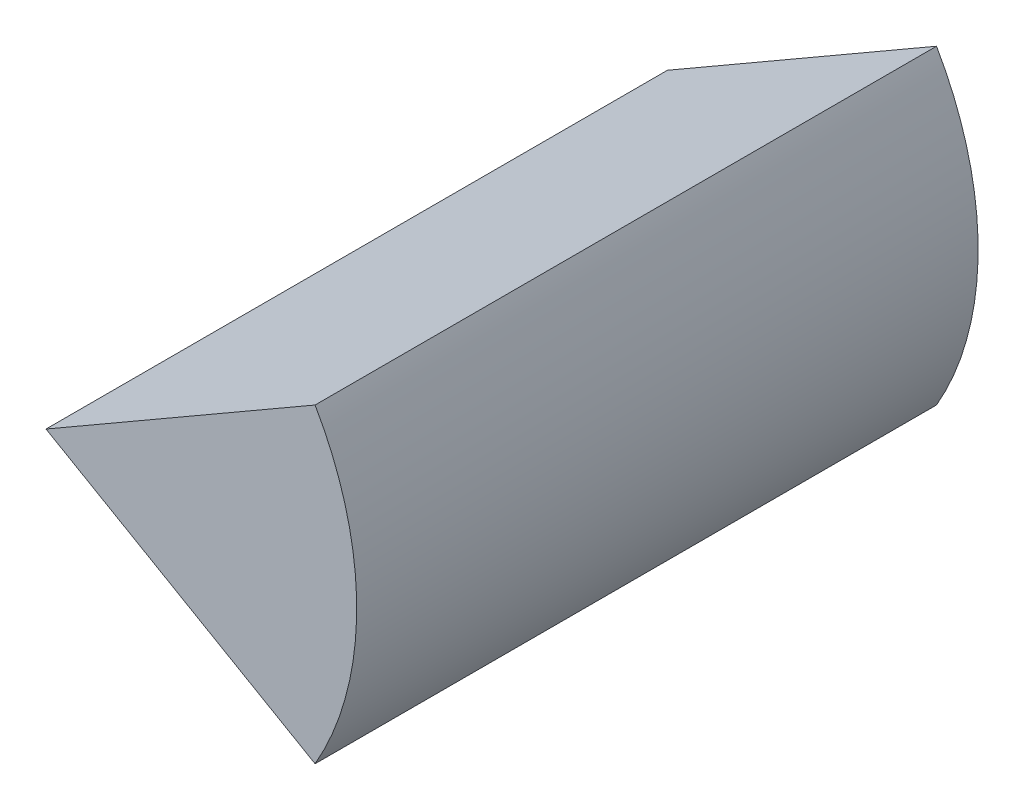
SolidWorks part; units mm, degrees
ref_plane "Alzado" through (0, 0, 0) normal (0, 0, 1) x (1, 0, 0)
ref_plane "Planta" through (0, 0, 0) normal (0, 1, 0) x (1, 0, 0)
ref_plane "Vista lateral" through (0, 0, 0) normal (1, 0, 0) x (0, 0, -1)
sketch "Croquis1" plane through (0, 0, 0) normal (0, 0, 1) x (1, 0, 0)
  line L2 (0, 0) -> (21.6506, 12.5)
  line L3 (0, 0) -> (21.6506, -12.5)
  arc A0 (21.6506, -12.5) -> (21.6506, 12.5) centre (0, 0) ccw
  dimension "D1" = 50
  dimension "D3" = 60
extrude "Saliente-Extruir1" add sketch "Croquis1" along normal blind 50
sketch "Croquis2" plane through (0, 0, 0) normal (0, 0, -1) x (-1, 0, 0)
  circle A0 centre (-15.9212, 0.3661) radius 5
  dimension "D1" = 10
extrude "Cortar-Extruir1" cut sketch "Croquis2" against normal blind 10
